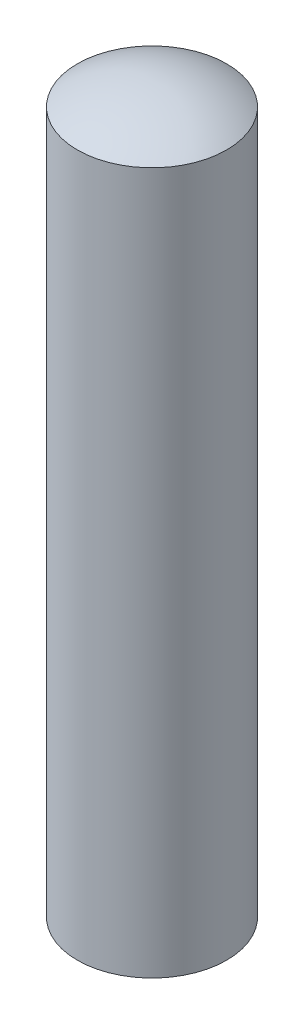
SolidWorks part; units mm, degrees
material "Plain Carbon Steel"
ref_plane "Front Plane" through (0, 0, 0) normal (0, 0, 1) x (1, 0, 0)
ref_plane "Top Plane" through (0, 0, 0) normal (0, 1, 0) x (1, 0, 0)
ref_plane "Right Plane" through (0, 0, 0) normal (1, 0, 0) x (0, 0, -1)
other "Configuration Table"
sketch "Sketch1" plane through (0, 0, 0) normal (0, 0, 1) x (1, 0, 0)
  line L0 (0, 5) -> (0, -45) construction
  line L1 (4, -1.2) -> (-4, -1.2) construction
  line L2 (4, -1.2) -> (4, -38.8)
  line L3 (4, -38.8) -> (-4, -38.8) construction
  line L4 (4, -40) -> (-4, -40) construction
  line L5 (0, -40) -> (0, 0)
  arc A0 (0, 0) -> (4, -1.2) centre (0, -7.2667) cw
  arc A1 (-4, -1.2) -> (0, 0) centre (0, -7.2667) cw construction
  arc A2 (4, -38.8) -> (0, -40) centre (0, -32.7333) cw
  arc A3 (0, -40) -> (-4, -38.8) centre (0, -32.7333) cw construction
  dimension "D1" = 1.2
  dimension "D2" = 8
  dimension "D3" = 1.2
  dimension "D4" = 5
  dimension "D5" = 5
  dimension "Length" = 40
revolve "Revolve1" add sketch "Sketch1" angle 360 about L0
